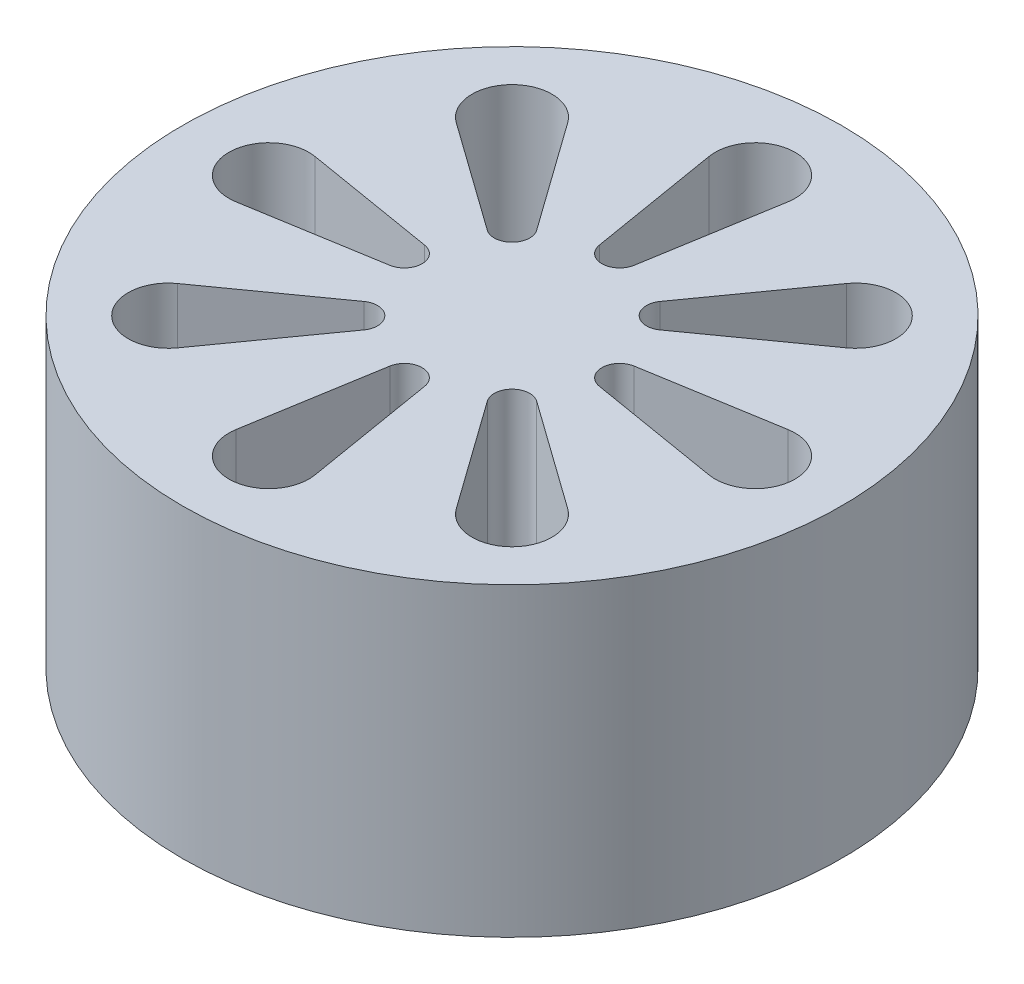
SolidWorks part; units mm, degrees
ref_plane "Front Plane" through (0, 0, 0) normal (0, 0, 1) x (1, 0, 0)
ref_plane "Top Plane" through (0, 0, 0) normal (0, 1, 0) x (1, 0, 0)
ref_plane "Right Plane" through (0, 0, 0) normal (1, 0, 0) x (0, 0, -1)
sketch "Sketch1" plane through (0, 0, 0) normal (0, 1, 0) x (1, 0, 0)
  circle A0 centre (0, 0) radius 27.94
  dimension "D1" = 55.88
extrude "Boss-Extrude1" add sketch "Sketch1" along normal blind 25.89
sketch "Sketch2" plane through (0, 0, 0) normal (0, -1, 0) x (1, 0, 0)
  line L0 (0, 0) -> (58.348, 0) construction
  line L1 (0, 7.6241) -> (0, 24) construction
  line L2 (1.4796, 8.8775) -> (3.3424, 20.0544)
  line L4 (-3.3424, 20.0544) -> (-1.4796, 8.8775)
  line L5 (7.3236, 5.2311) -> (16.5441, 11.8172)
  line L6 (11.8172, 16.5441) -> (5.2311, 7.3236)
  line L7 (5.3911, 5.3911) -> (16.9706, 16.9706) construction
  line L8 (8.8775, -1.4796) -> (20.0544, -3.3424)
  line L9 (20.0544, 3.3424) -> (8.8775, 1.4796)
  line L10 (7.6241, 0) -> (24, 0) construction
  line L11 (5.2311, -7.3236) -> (11.8172, -16.5441)
  line L12 (16.5441, -11.8172) -> (7.3236, -5.2311)
  line L13 (5.3911, -5.3911) -> (16.9706, -16.9706) construction
  line L14 (-1.4796, -8.8775) -> (-3.3424, -20.0544)
  line L15 (3.3424, -20.0544) -> (1.4796, -8.8775)
  line L16 (0, -7.6241) -> (0, -24) construction
  line L17 (-7.3236, -5.2311) -> (-16.5441, -11.8172)
  line L18 (-11.8172, -16.5441) -> (-5.2311, -7.3236)
  line L19 (-5.3911, -5.3911) -> (-16.9706, -16.9706) construction
  line L20 (-8.8775, 1.4796) -> (-20.0544, 3.3424)
  line L21 (-20.0544, -3.3424) -> (-8.8775, -1.4796)
  line L22 (-7.6241, 0) -> (-24, 0) construction
  line L23 (-5.2311, 7.3236) -> (-11.8172, 16.5441)
  line L24 (-16.5441, 11.8172) -> (-7.3236, 5.2311)
  line L25 (-5.3911, 5.3911) -> (-16.9706, 16.9706) construction
  arc A0 (-1.4796, 8.8775) -> (1.4796, 8.8775) centre (0, 9.1241) ccw
  arc A1 (3.3424, 20.0544) -> (-3.3424, 20.0544) centre (0, 20.6115) ccw
  arc A2 (5.2311, 7.3236) -> (7.3236, 5.2311) centre (6.4517, 6.4517) ccw
  arc A3 (16.5441, 11.8172) -> (11.8172, 16.5441) centre (14.5745, 14.5745) ccw
  arc A4 (8.8775, 1.4796) -> (8.8775, -1.4796) centre (9.1241, 0) ccw
  arc A5 (20.0544, -3.3424) -> (20.0544, 3.3424) centre (20.6115, 0) ccw
  arc A6 (7.3236, -5.2311) -> (5.2311, -7.3236) centre (6.4517, -6.4517) ccw
  arc A7 (11.8172, -16.5441) -> (16.5441, -11.8172) centre (14.5745, -14.5745) ccw
  arc A8 (1.4796, -8.8775) -> (-1.4796, -8.8775) centre (0, -9.1241) ccw
  arc A9 (-3.3424, -20.0544) -> (3.3424, -20.0544) centre (0, -20.6115) ccw
  arc A10 (-5.2311, -7.3236) -> (-7.3236, -5.2311) centre (-6.4517, -6.4517) ccw
  arc A11 (-16.5441, -11.8172) -> (-11.8172, -16.5441) centre (-14.5745, -14.5745) ccw
  arc A12 (-8.8775, -1.4796) -> (-8.8775, 1.4796) centre (-9.1241, 0) ccw
  arc A13 (-20.0544, 3.3424) -> (-20.0544, -3.3424) centre (-20.6115, 0) ccw
  arc A14 (-7.3236, 5.2311) -> (-5.2311, 7.3236) centre (-6.4517, 6.4517) ccw
  arc A15 (-11.8172, 16.5441) -> (-16.5441, 11.8172) centre (-14.5745, 14.5745) ccw
  point P3 (0, 0)
  point P5 (0, 0)
  point P69 (0, 0)
  dimension "D4" = 3
  dimension "D5" = 3.3885
  dimension "D1" = 8
  dimension "D2" = 7.6241
  dimension "D3" = 16.3759
  dimension "D6" = 18.925
  dimension "D7" = 11.1769
extrude "Cut-Extrude2" cut sketch "Sketch2" against normal through all
sketch "Sketch4" plane through (0, 0, 0) normal (0, -1, 0) x (-1, 0, 0)
  circle A0 centre (0, 0) radius 4.5
  circle A1 centre (0, 0) radius 2
  dimension "D1" = 4
  dimension "D2" = 9
extrude "Boss-Extrude3" add sketch "Sketch4" along normal blind 7
